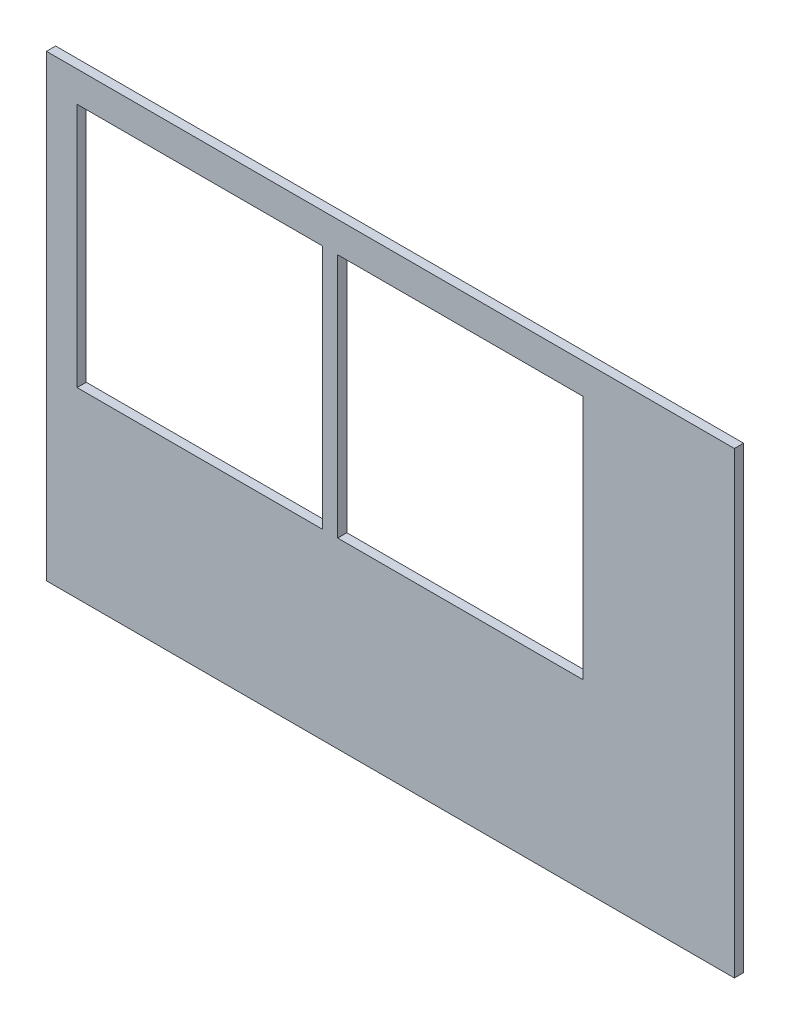
SolidWorks part; units mm, degrees
ref_plane "Front Plane" through (0, 0, 0) normal (0, 0, 1) x (1, 0, 0)
ref_plane "Top Plane" through (0, 0, 0) normal (0, 1, 0) x (1, 0, 0)
ref_plane "Right Plane" through (0, 0, 0) normal (1, 0, 0) x (0, 0, -1)
sketch "Sketch1" plane through (0, 0, 0) normal (0, 0, 1) x (1, 0, 0)
  line L0 (1980.3459, 600) -> (1980.3459, 560) construction
  line L1 (1435.3469, 0) -> (535.3469, 0)
  line L2 (1435.3469, 0) -> (1435.3469, 600)
  line L3 (1435.3469, 600) -> (535.3469, 600)
  line L4 (535.3469, 0) -> (535.3469, 600)
  line L5 (1237.3469, 560) -> (916.3469, 560)
  line L6 (1237.3469, 560) -> (1237.3469, 239)
  line L7 (1237.3469, 239) -> (916.3469, 239)
  line L8 (916.3469, 560) -> (916.3469, 239)
  line L9 (896.3469, 239) -> (575.3469, 239)
  line L10 (896.3469, 239) -> (896.3469, 560)
  line L11 (896.3469, 560) -> (575.3469, 560)
  line L12 (575.3469, 239) -> (575.3469, 560)
  line L13 (826.0931, 600) -> (826.0931, 560) construction
  line L14 (1435.3469, 0) -> (1435.3469, 600) construction
  line L15 (535.3469, 389.3449) -> (575.3469, 389.3449) construction
  line L16 (916.3469, 352.8762) -> (896.3469, 352.8762) construction
  line L17 (535.3469, 600) -> (1435.3469, 600) construction
  dimension "D1" = 321
  dimension "D3" = 321
  dimension "D4" = 40
  dimension "D5" = 20
  dimension "D6" = 40
extrude "Boss-Extrude1" add sketch "Sketch1" along normal blind 12
